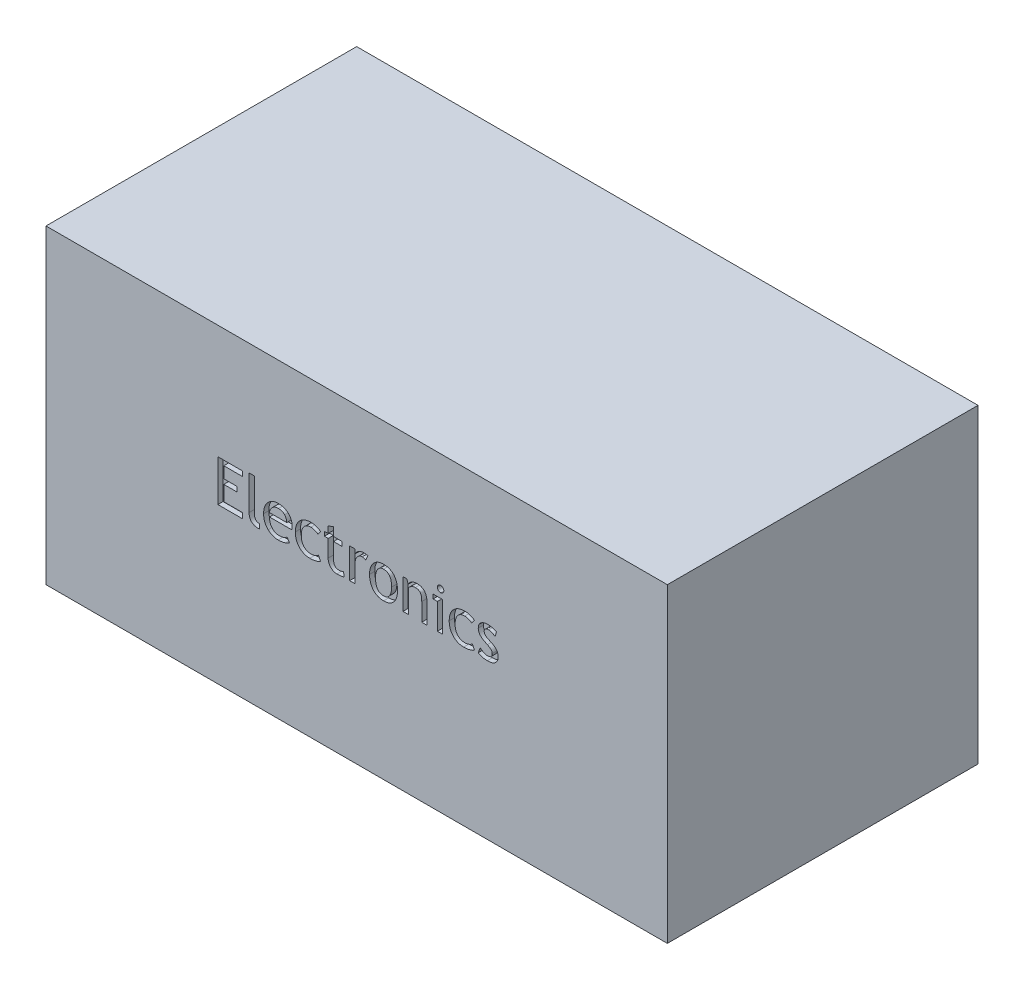
SolidWorks part; units mm, degrees
ref_plane "Front Plane" through (0, 0, 0) normal (0, 0, 1) x (1, 0, 0)
ref_plane "Top Plane" through (0, 0, 0) normal (0, 1, 0) x (1, 0, 0)
ref_plane "Right Plane" through (0, 0, 0) normal (1, 0, 0) x (0, 0, -1)
sketch "Sketch1" plane through (0, 0, 0) normal (0, 1, 0) x (1, 0, 0)
  line L1 (-762, -381) -> (762, -381)
  line L2 (-762, -381) -> (-762, 381)
  line L3 (-762, 381) -> (762, 381)
  line L4 (762, -381) -> (762, 381)
  line L5 (-762, -381) -> (762, 381) construction
  line L6 (-762, 381) -> (762, -381) construction
  point P0 (0, 0)
  dimension "D1" = 1524
  dimension "D2" = 762
extrude "Boss-Extrude1" add sketch "Sketch1" along normal blind 762
sketch "Sketch2" plane through (0, 0, 381) normal (0, 0, 1) x (1, 0, 0)
  line L0 (-762, 381) -> (762, 381) construction
  line L1 (-762, 762) -> (-762, 0) construction
  line L2 (762, 762) -> (762, 0) construction
  text T0 "Electronics" font "Trebuchet MS" height 101.6
extrude "Cut-Extrude1" cut sketch "Sketch2" against normal blind 12.7
